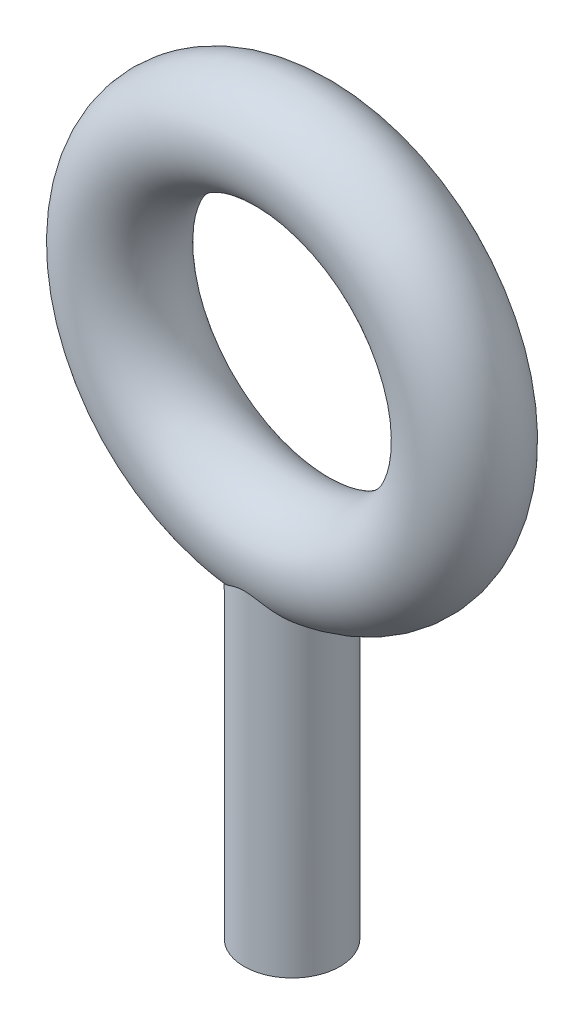
SolidWorks part; units mm, degrees
material "Tin Bearing Bronze"
ref_plane "Front Plane" through (0, 0, 0) normal (0, 0, 1) x (1, 0, 0)
ref_plane "Top Plane" through (0, 0, 0) normal (0, 1, 0) x (1, 0, 0)
ref_plane "Right Plane" through (0, 0, 0) normal (1, 0, 0) x (0, 0, -1)
sketch "Sketch1" plane through (0, 0, 0) normal (1, 0, 0) x (0, 0, -1)
  line L0 (0, 55) -> (0, -55) construction
  line L1 (55, 0) -> (-55, 0) construction
  line L2 (-14.7609, 0) -> (18.2634, 0) construction
  circle A0 centre (0, -15.875) radius 4.7625
  dimension "D1" = 9.525
  dimension "D2" = 15.875
revolve "Revolve1" add sketch "Sketch1" angle 360 about L2
ref_plane "Plane1" through (0, -15.875, 0) normal (0, 1, 0) x (1, 0, 0)
sketch "Sketch2" plane through (0, -15.875, 0) normal (0, 1, 0) x (1, 0, 0)
  circle A0 centre (0, 0) radius 4.4132
  dimension "D1" = 8.8265
extrude "Boss-Extrude1" add sketch "Sketch2" against normal blind 31.75
